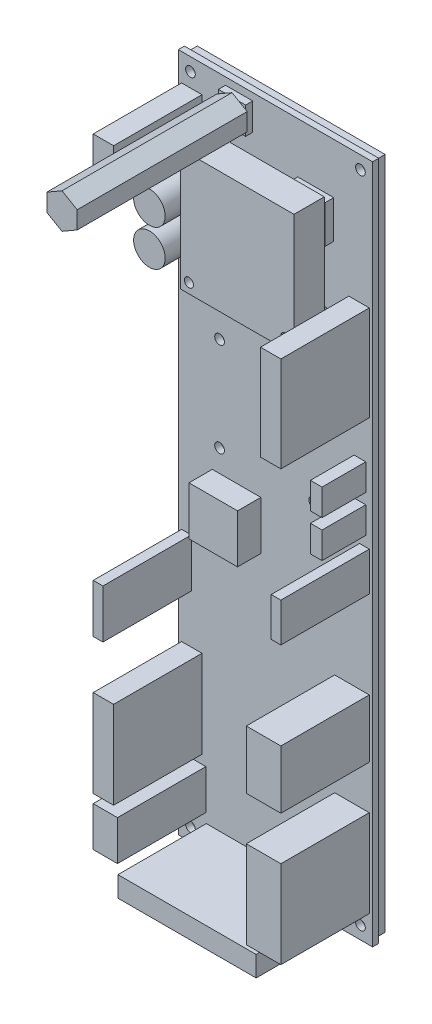
SolidWorks part; units mm, degrees
material "G-10 Garolite"
ref_plane "Front Plane" through (0, 0, 0) normal (0, 0, 1) x (1, 0, 0)
ref_plane "Top Plane" through (0, 0, 0) normal (0, 1, 0) x (1, 0, 0)
ref_plane "Right Plane" through (0, 0, 0) normal (1, 0, 0) x (0, 0, -1)
sketch "Feed thru Layout" plane through (0, 0, 0) normal (0, 1, 0) x (1, 0, 0)
  line L0 (8.3132, -14.5253) -> (21.1116, -28.6357) construction
  line L1 (-6.2893, -13.8134) -> (-20.3997, -26.6118) construction
  line L2 (20.3997, -43.2382) -> (6.2893, -56.0366) construction
  line L3 (-21.1116, -41.2143) -> (-8.3132, -55.3247) construction
  line L4 (-13.3445, -20.2126) -> (13.3445, -49.6374) construction
  line L5 (-7.051, 40.3313) -> (-7.051, 56.9744) construction
  line L6 (0, 0) -> (-20.32, 33.1636) construction
  line L7 (0, 0) -> (0, -34.925) construction
  line L8 (0, -34.925) -> (0, -53.975) construction
  line L9 (0, -53.975) -> (0, -48.9106) construction
  line L10 (0, 0) -> (-38.7744, -3.0448) construction
  line L11 (38.7744, -3.0448) -> (-38.7744, -3.0448) construction
  circle A0 centre (0, 0) radius 38.8938 construction
  circle A1 centre (-38.7744, -3.0448) radius 15.0749
  circle A2 centre (-20.32, 33.1636) radius 15.0813
  circle A3 centre (20.32, 33.1636) radius 15.0749
  circle A4 centre (38.7744, -3.0448) radius 15.0749
  circle A5 centre (-38.7744, -3.0448) radius 20.32 construction
  circle A6 centre (-20.32, 33.1636) radius 20.32 construction
  circle A7 centre (20.32, 33.1636) radius 20.32 construction
  circle A8 centre (38.7744, -3.0448) radius 20.32 construction
  circle A9 centre (0, -34.925) radius 9.525
  circle A10 centre (-20.32, 33.1636) radius 11.115 construction
  circle A11 centre (0, 0) radius 25.4 construction
  circle A12 centre (0, -34.925) radius 19.05
  circle A13 centre (0, -34.925) radius 23.8082 construction
  arc A14 (-8.3132, -55.3247) -> (6.2893, -56.0366) centre (-0.656, -48.3794) ccw construction
  circle A15 centre (0, -34.925) radius 35.1227
  arc A17 (20.3997, -43.2382) -> (21.1116, -28.6357) centre (13.4544, -35.581) ccw construction
  arc A18 (8.3132, -14.5253) -> (-6.2893, -13.8134) centre (0.656, -21.4706) ccw construction
  arc A19 (-20.3997, -26.6118) -> (-21.1116, -41.2143) centre (-13.4544, -34.269) ccw construction
  circle A22 centre (0, 0) radius 12.7
  point P2 (0, 0)
  point P19 (0, 0)
  point P42 (28.0569, -36.2929)
  point P45 (1.3679, -6.8681)
  point P52 (0, -34.925)
  dimension "D1" = 30.1498
  dimension "D2" = 5.2451
  dimension "D3" = 22.23
  dimension "D4" = 50.8
  dimension "D5" = 30.1625
  dimension "D6" = 19.05
  dimension "D7" = 34.925
  dimension "D8" = 38.1
  dimension "D10" = 10.3378
  dimension "D11" = 47.6164
  dimension "D12" = 77.7875
  dimension "D14" = 85.51
  dimension "D16" = 25.4
  dimension "D13" = 62.993
  dimension "D17" = 40.64
  dimension "D9" = 39.7256
sketch "Sketch1" plane through (0, 0, 0) normal (0, 1, 0) x (-1, 0, 0)
  line L0 (0, 0) -> (0, -42.8625) construction
  line L1 (0, 0) -> (32.8346, 27.5515) construction
  line L2 (0, 0) -> (-32.8346, 27.5515) construction
  line L3 (0, 0) -> (60.325, 0) construction
  line L4 (33.6366, 23.0029) -> (37.1748, 25.9718) construction
  line L5 (37.1748, 25.9718) -> (36.3728, 30.5204) construction
  line L6 (36.3728, 30.5204) -> (32.0325, 32.1001) construction
  line L7 (32.0325, 32.1001) -> (28.4943, 29.1312) construction
  line L8 (28.4943, 29.1312) -> (29.2964, 24.5826) construction
  line L9 (29.2964, 24.5826) -> (33.6366, 23.0029) construction
  circle A0 centre (0, 0) radius 55.5625
  circle A1 centre (0, 0) radius 14.2875
  circle A2 centre (0, 0) radius 42.8625 construction
  circle A3 centre (32.8346, 27.5515) radius 4 construction
  circle A4 centre (32.8346, 27.5515) radius 4.6188 construction
  circle A5 centre (0, 0) radius 38.8938 construction
  circle A6 centre (-32.8346, 27.5515) radius 4.6188 construction
  circle A7 centre (0, -42.8625) radius 4.6188 construction
  circle A9 centre (0, -42.8625) radius 8.2285 construction
  circle A12 centre (20.32, -33.1636) radius 14.2875
  circle A13 centre (-20.32, -33.1636) radius 14.2875
  point P2 (0, 0)
  dimension "D1" = 28.575
  dimension "D2" = 111.125
  dimension "D5" = 8
  dimension "D6" = 85.725
  dimension "D8" = 28.575
  dimension "D9" = 16.4571
  dimension "D3" = 100
  dimension "D4" = 130
  dimension "D7" = 90
ref_plane "Plane1" through (0, 0, -34.925) normal (0, 0, 1) x (1, 0, 0)
sketch "Sketch3" plane through (0, 0, -34.925) normal (0, 0, 1) x (1, 0, 0)
  line L0 (0, 88.9) -> (0, -88.9) construction
  line L1 (-25.4, 88.9) -> (25.4, 88.9)
  line L2 (-25.4, 88.9) -> (-25.4, -88.9)
  line L3 (-25.4, -88.9) -> (25.4, -88.9)
  line L4 (25.4, 88.9) -> (25.4, -88.9)
  line L5 (-11.9507, 48.0187) -> (13.0683, 48.0187) construction
  line L6 (-22.225, 85.4964) -> (22.225, 85.4964) construction
  line L7 (-22.225, 85.4964) -> (-22.225, -85.4964) construction
  line L8 (-22.225, -85.4964) -> (22.225, -85.4964) construction
  line L9 (22.225, 85.4964) -> (22.225, -85.4964) construction
  line L10 (-14.605, 28.702) -> (10.0076, 28.702) construction
  line L11 (-14.605, 28.702) -> (-14.605, 4.0894) construction
  line L12 (-14.605, 4.0894) -> (10.0076, 4.0894) construction
  line L13 (10.0076, 28.702) -> (10.0076, 4.0894) construction
  circle A0 centre (22.225, 85.4964) radius 1.27
  circle A1 centre (-22.225, 85.4964) radius 1.27
  circle A2 centre (22.225, -85.4964) radius 1.27
  circle A3 centre (-22.225, -85.4964) radius 1.27
  circle A4 centre (-14.605, 28.702) radius 1.27
  circle A5 centre (10.0076, 28.702) radius 1.27
  circle A6 centre (-14.605, 4.0894) radius 1.27
  circle A7 centre (10.0076, 4.0894) radius 1.27
  circle A8 centre (-11.9507, 48.0187) radius 1.8415
  circle A9 centre (13.0683, 48.0187) radius 1.8415
  point P15 (-20.955, 85.4964)
  point P16 (20.955, 85.4964)
  point P17 (0, 85.4964)
  point P18 (-22.225, -86.7664)
  point P19 (-22.225, 86.7664)
  point P20 (-22.225, 0)
  point P29 (-13.335, 28.702)
  point P30 (8.7376, 28.702)
  point P31 (10.0076, 29.972)
  point P32 (-15.875, 28.702)
  point P37 (-10.1092, 48.0187)
  point P38 (11.2268, 48.0187)
  point P39 (13.0683, 49.8602)
  point P40 (-13.7922, 48.0187)
  dimension "D3" = 2.54
  dimension "D5" = 41.91
  dimension "D4" = 44.45
  dimension "D7" = 2.54
  dimension "D9" = 24.6126
  dimension "D12" = 3.683
  dimension "D1" = 50.8
  dimension "D2" = 177.8
  dimension "D6" = 173.5328
  dimension "D8" = 22.0726
  dimension "D10" = 58.928
  dimension "D11" = 9.525
  dimension "D13" = 21.336
  dimension "D14" = 11.6078
  dimension "D15" = 39.0398
extrude "Boss-Extrude1" add sketch "Sketch3" along normal blind 1.6002
sketch "Sketch4" plane through (0, 0, -33.3248) normal (0, 0, 1) x (1, 0, 0)
  line L0 (-25.4, 88.9) -> (-25.4, -88.9) construction
  line L1 (-24.5364, 81.788) -> (-19.2024, 81.788)
  line L2 (-24.5364, 81.788) -> (-24.5364, 71.374)
  line L3 (-24.5364, 71.374) -> (-19.2024, 71.374)
  line L4 (-19.2024, 81.788) -> (-19.2024, 71.374)
  line L5 (-24.5364, -19.304) -> (-21.9964, -19.304)
  line L6 (-24.5364, -19.304) -> (-24.5364, -32.004)
  line L7 (-24.5364, -32.004) -> (-21.9964, -32.004)
  line L8 (-21.9964, -19.304) -> (-21.9964, -32.004)
  line L9 (-24.5364, -44.704) -> (-19.2024, -44.704)
  line L10 (-24.5364, -44.704) -> (-24.5364, -67.564)
  line L11 (-24.5364, -67.564) -> (-19.2024, -67.564)
  line L12 (-19.2024, -44.704) -> (-19.2024, -67.564)
  line L13 (-24.5364, -69.85) -> (-18.1864, -69.85)
  line L14 (-24.5364, -69.85) -> (-24.5364, -80.264)
  line L15 (-24.5364, -80.264) -> (-18.1864, -80.264)
  line L16 (-18.1864, -69.85) -> (-18.1864, -80.264)
  line L17 (-18.0721, -82.7024) -> (18.0721, -82.7024)
  line L18 (-18.0721, -82.7024) -> (-18.0721, -88.0364)
  line L19 (-18.0721, -88.0364) -> (18.0721, -88.0364)
  line L20 (18.0721, -82.7024) -> (18.0721, -88.0364)
  line L21 (15.494, -58.928) -> (24.5364, -58.928)
  line L22 (15.494, -58.928) -> (15.494, -81.788)
  line L23 (15.494, -81.788) -> (24.5364, -81.788)
  line L24 (24.5364, -58.928) -> (24.5364, -81.788)
  line L25 (15.494, -32.258) -> (24.5364, -32.258)
  line L26 (15.494, -32.258) -> (15.494, -47.498)
  line L27 (15.494, -47.498) -> (24.5364, -47.498)
  line L28 (24.5364, -32.258) -> (24.5364, -47.498)
  line L29 (21.9964, 0.762) -> (24.5364, 0.762)
  line L30 (21.9964, 0.762) -> (21.9964, -9.398)
  line L31 (21.9964, -9.398) -> (24.5364, -9.398)
  line L32 (24.5364, 0.762) -> (24.5364, -9.398)
  line L33 (19.2024, 55.372) -> (24.5364, 55.372)
  line L34 (19.2024, 55.372) -> (19.2024, 30.48)
  line L35 (19.2024, 30.48) -> (24.5364, 30.48)
  line L36 (24.5364, 55.372) -> (24.5364, 30.48)
  line L37 (25.4, -88.9) -> (25.4, 88.9) construction
  line L38 (-25.4, -88.9) -> (25.4, -88.9) construction
  line L39 (0, -88.0364) -> (0, -88.9) construction
  line L40 (25.4, 88.9) -> (-25.4, 88.9) construction
  dimension "D1" = 5.334
  dimension "D2" = 0.8636
  dimension "D3" = 0.8636
  dimension "D4" = 0.8636
  dimension "D5" = 36.1442
  dimension "D6" = 7.112
  dimension "D7" = 10.414
  dimension "D8" = 108.204
  dimension "D9" = 12.7
  dimension "D10" = 2.54
  dimension "D11" = 22.86
  dimension "D12" = 21.336
  dimension "D13" = 8.636
  dimension "D14" = 6.35
  dimension "D15" = 10.414
  dimension "D16" = 7.112
  dimension "D17" = 9.0424
  dimension "D18" = 22.86
  dimension "D19" = 41.402
  dimension "D20" = 15.24
  dimension "D21" = 88.138
  dimension "D22" = 10.16
  dimension "D23" = 24.892
  dimension "D24" = 33.528
extrude "Boss-Extrude2" add sketch "Sketch4" along normal blind 23.114 separate body
sketch "Sketch5" plane through (0, 0, -33.3248) normal (0, 0, 1) x (1, 0, 0)
  line L0 (25.4, 88.9) -> (-25.4, 88.9) construction
  line L1 (20.574, 20.066) -> (23.622, 20.066)
  line L2 (20.574, 20.066) -> (20.574, 13.1318)
  line L3 (20.574, 13.1318) -> (23.622, 13.1318)
  line L4 (23.622, 20.066) -> (23.622, 13.1318)
  line L5 (20.574, 10.3378) -> (23.622, 10.3378)
  line L6 (20.574, 10.3378) -> (20.574, 3.4036)
  line L7 (20.574, 3.4036) -> (23.622, 3.4036)
  line L8 (23.622, 10.3378) -> (23.622, 3.4036)
  line L9 (25.4, -88.9) -> (25.4, 88.9) construction
  dimension "D1" = 68.834
  dimension "D2" = 3.048
  dimension "D3" = 6.9342
  dimension "D4" = 2.794
  dimension "D5" = 1.778
extrude "Boss-Extrude3" add sketch "Sketch5" along normal blind 11.43 separate body
sketch "Sketch6" plane through (0, 0, -33.3248) normal (0, 0, 1) x (1, 0, 0)
  line L0 (-25.4, 88.9) -> (-25.4, -88.9) construction
  line L1 (25.4, 88.9) -> (-25.4, 88.9) construction
  circle A0 centre (-20.2565, 62.1665) radius 4.1275
  circle A1 centre (-20.2565, 52.6415) radius 4.1275
  point P4 (-20.2565, 66.294)
  point P5 (-20.2565, 48.514)
  point P6 (-24.384, 62.1665)
  point P11 (0, 0)
  dimension "D1" = 8.255
  dimension "D2" = 17.78
  dimension "D3" = 1.016
  dimension "D4" = 22.606
extrude "Boss-Extrude4" add sketch "Sketch6" along normal blind 12.7 separate body
sketch "Sketch7" plane through (0, 0, -33.3248) normal (0, 0, 1) x (1, 0, 0)
  line L0 (-25.4, 88.9) -> (-25.4, -88.9) construction
  line L1 (-16.51, -1.7018) -> (-3.81, -1.7018)
  line L2 (-16.51, -1.7018) -> (-16.51, -14.4018)
  line L3 (-16.51, -14.4018) -> (-3.81, -14.4018)
  line L4 (-3.81, -1.7018) -> (-3.81, -14.4018)
  line L5 (25.4, 88.9) -> (-25.4, 88.9) construction
  dimension "D1" = 12.7
  dimension "D2" = 8.89
  dimension "D3" = 90.6018
extrude "Boss-Extrude5" add sketch "Sketch7" along normal blind 6.096 separate body
sketch "Sketch8" plane through (0, 0, -33.3248) normal (0, 0, 1) x (1, 0, 0)
  line L0 (25.4, -88.9) -> (25.4, 88.9) construction
  line L1 (5.842, 75.692) -> (15.24, 75.692)
  line L2 (5.842, 75.692) -> (5.842, 65.786)
  line L3 (5.842, 65.786) -> (15.24, 65.786)
  line L4 (15.24, 75.692) -> (15.24, 65.786)
  line L5 (25.4, 88.9) -> (-25.4, 88.9) construction
  dimension "D1" = 10.16
  dimension "D2" = 13.208
  dimension "D3" = 9.906
  dimension "D4" = 9.398
extrude "Boss-Extrude6" add sketch "Sketch8" along normal blind 2.286 separate body
sketch "Sketch9" plane through (0, 0, -33.3248) normal (0, 0, 1) x (1, 0, 0)
  line L0 (25.4, 88.9) -> (-25.4, 88.9) construction
  line L1 (-13.0556, 86.995) -> (-5.9436, 86.995)
  line L2 (-13.0556, 86.995) -> (-13.0556, 79.883)
  line L3 (-13.0556, 79.883) -> (-5.9436, 79.883)
  line L4 (-5.9436, 86.995) -> (-5.9436, 79.883)
  line L5 (-25.4, 88.9) -> (-25.4, -88.9) construction
  dimension "D1" = 7.112
  dimension "D2" = 1.905
  dimension "D3" = 12.3444
extrude "Boss-Extrude7" add sketch "Sketch9" along normal blind 1.8542 separate body
sketch "Sketch10" plane through (0, 0, -31.4706) normal (0, 0, 1) x (1, 0, 0)
  line L0 (-9.4996, 86.995) -> (-9.4996, 79.883) construction
  line L1 (-5.9436, 86.995) -> (-13.0556, 86.995) construction
  line L2 (-13.0556, 79.883) -> (-5.9436, 79.883) construction
  line L4 (-5.5245, 81.144) -> (-5.5245, 85.734)
  line L5 (-5.5245, 85.734) -> (-9.4996, 88.0291)
  line L6 (-9.4996, 88.0291) -> (-13.4747, 85.734)
  line L7 (-13.4747, 85.734) -> (-13.4747, 81.144)
  line L8 (-13.4747, 81.144) -> (-9.4996, 78.8489)
  line L9 (-9.4996, 78.8489) -> (-5.5245, 81.144)
  circle A1 centre (-9.4996, 83.439) radius 3.9751 construction
  point P7 (0, 0)
  dimension "D1" = 7.9502
extrude "Boss-Extrude8" add sketch "Sketch10" along normal blind 44.45
sketch "Sketch11" plane through (0, 0, -34.925) normal (0, 0, -1) x (-1, 0, 0)
  line L0 (25.4, 88.9) -> (25.4, -88.9) construction
  line L1 (-24.5618, 88.0618) -> (24.5618, 88.0618)
  line L2 (-24.5618, 88.0618) -> (-24.5618, -88.0618)
  line L3 (-24.5618, -88.0618) -> (24.5618, -88.0618)
  line L4 (24.5618, 88.0618) -> (24.5618, -88.0618)
  line L5 (-25.4, -88.9) -> (-25.4, 88.9) construction
  line L6 (-25.4, 88.9) -> (25.4, 88.9) construction
  line L7 (25.4, -88.9) -> (-25.4, -88.9) construction
  circle A0 centre (-13.0683, 48.0187) radius 1.8415
  circle A1 centre (11.9507, 48.0187) radius 1.8415
  circle A2 centre (-10.0076, 28.702) radius 1.27
  circle A3 centre (14.605, 28.702) radius 1.27
  circle A4 centre (-10.0076, 4.0894) radius 1.27
  circle A5 centre (14.605, 4.0894) radius 1.27
  circle A6 centre (-22.225, -85.4964) radius 1.27
  circle A7 centre (22.225, -85.4964) radius 1.27
  circle A8 centre (22.225, 85.4964) radius 1.27
  circle A9 centre (-22.225, 85.4964) radius 1.27
  circle A10 centre (-22.225, -85.4964) radius 1.27 construction
  circle A11 centre (14.605, 4.0894) radius 1.27 construction
  circle A13 centre (11.9507, 48.0187) radius 1.8415 construction
  dimension "D1" = 0.8382
  dimension "D2" = 0.8382
  dimension "D3" = 0.8382
  dimension "D4" = 0.8382
extrude "Boss-Extrude9" add sketch "Sketch11" along normal blind 2.54 separate body
ref_plane "Plane2" through (0, 0, -30.7848) normal (0, 0, 1) x (1, 0, 0)
sketch "Sketch13" plane through (0, 0, -30.7848) normal (0, 0, 1) x (1, 0, 0)
  line L0 (-12.1539, 48.0187) -> (13.0683, 48.0187) construction
  line L1 (-14.4018, 77.1906) -> (15.3162, 77.1906)
  line L2 (-14.4018, 77.1906) -> (-14.4018, 45.4406)
  line L3 (-14.4018, 45.4406) -> (15.3162, 45.4406)
  line L4 (15.3162, 77.1906) -> (15.3162, 45.4406)
  line L5 (0.4572, 45.4406) -> (0.4572, 48.0187) construction
  circle A0 centre (-12.1539, 48.0187) radius 1.1811
  circle A1 centre (13.0683, 48.0187) radius 1.1811
  circle A2 centre (13.0683, 48.0187) radius 1.8415 construction
  point P10 (-10.9728, 48.0187)
  point P11 (11.8872, 48.0187)
  point P12 (13.0683, 46.8376)
  dimension "D4" = 2.3622
  dimension "D1" = 31.75
  dimension "D2" = 29.718
  dimension "D3" = 22.86
  dimension "D5" = 1.397
extrude "Boss-Extrude10" add sketch "Sketch13" along normal blind 7.9248 separate body
